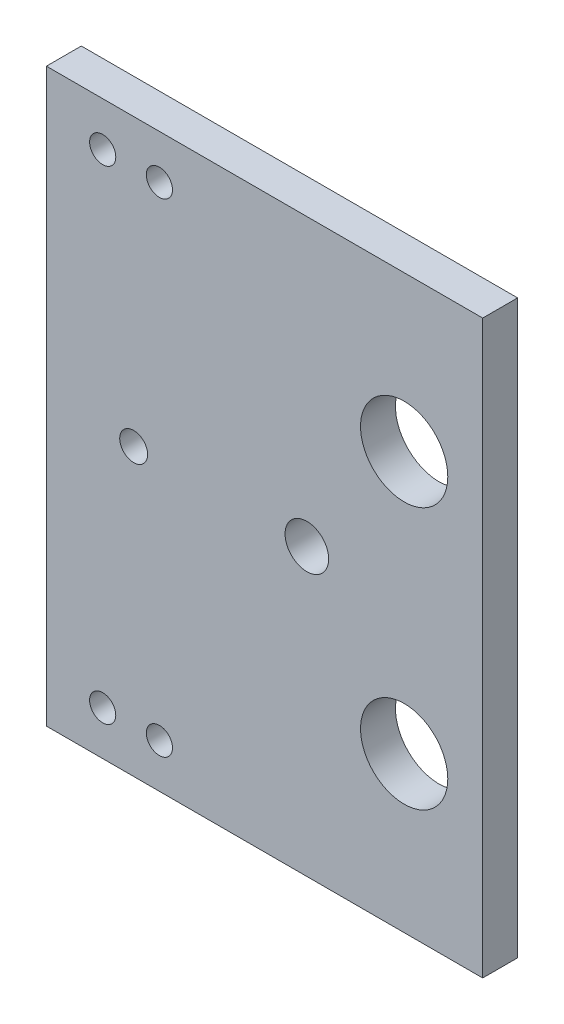
SolidWorks part; units mm, degrees
ref_plane "Płaszczyzna przednia" through (0, 0, 0) normal (0, 0, 1) x (1, 0, 0)
ref_plane "Płaszczyzna górna" through (0, 0, 0) normal (0, 1, 0) x (1, 0, 0)
ref_plane "Płaszczyzna prawa" through (0, 0, 0) normal (1, 0, 0) x (0, 0, -1)
sketch "Sketch1" plane through (0, 0, 0) normal (0, 0, 1) x (1, 0, 0)
  line L1 (0, 0) -> (-50, 0)
  line L2 (0, 0) -> (0, 65.5)
  line L3 (0, 65.5) -> (-50, 65.5)
  line L4 (-50, 0) -> (-50, 65.5)
  line L5 (0, 0) -> (-50, 65.5) construction
  line L6 (0, 65.5) -> (-50, 0) construction
  point P4 (-25, 32.75)
  dimension "D1" = 65.5
  dimension "D2" = 50
extrude "Boss-Extrude1" add sketch "Sketch1" along normal blind 4
sketch "Sketch4" plane through (0, 0, 4) normal (0, 0, 1) x (1, 0, 0)
  line L0 (0, 65.5) -> (-50, 65.5) construction
  line L1 (-50, 0) -> (0, 0) construction
  line L2 (0, 0) -> (0, 65.5) construction
  line L3 (-50, 65.5) -> (-50, 0) construction
  circle A0 centre (-9, 47.75) radius 5
  circle A1 centre (-37.05, 60.45) radius 1.5
  circle A2 centre (-43.55, 60.45) radius 1.5
  circle A3 centre (-40, 32.75) radius 1.6
  circle A4 centre (-20.15, 32.75) radius 2.5
  circle A5 centre (-9, 17.75) radius 5
  circle A6 centre (-37.05, 5.05) radius 1.5
  circle A7 centre (-43.55, 5.05) radius 1.5
  dimension "D1" = 10
  dimension "D2" = 10
  dimension "D3" = 17.75
  dimension "D4" = 17.75
  dimension "D5" = 32.75
  dimension "D6" = 9
  dimension "D7" = 9
  dimension "D8" = 20.15
  dimension "D9" = 5
  dimension "D10" = 3
  dimension "D11" = 3
  dimension "D12" = 3
  dimension "D13" = 3
  dimension "D14" = 6.45
  dimension "D15" = 6.45
  dimension "D16" = 6.5
  dimension "D17" = 6.5
  dimension "D18" = 5.05
  dimension "D19" = 5.05
  dimension "D20" = 5.05
  dimension "D21" = 5.05
  dimension "D22" = 3.2
  dimension "D23" = 32.75
  dimension "D24" = 10
extrude "Cut-Extrude2" cut sketch "Sketch4" against normal blind 10
